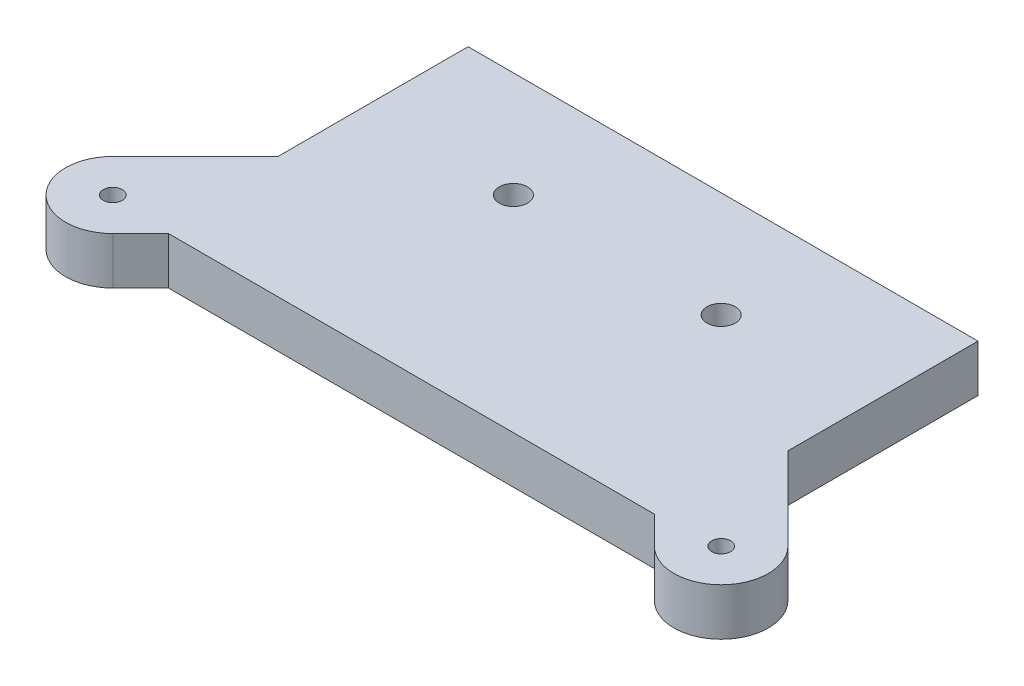
SolidWorks part; units mm, degrees
ref_plane "Front Plane" through (0, 0, 0) normal (0, 0, 1) x (1, 0, 0)
ref_plane "Top Plane" through (0, 0, 0) normal (0, 1, 0) x (1, 0, 0)
ref_plane "Right Plane" through (0, 0, 0) normal (1, 0, 0) x (0, 0, -1)
sketch "Sketch1" plane through (0, 0, 0) normal (0, 1, 0) x (1, 0, 0)
  line L1 (0, 0) -> (54, 0)
  line L2 (0, 0) -> (0, 33)
  line L3 (0, 33) -> (54, 33)
  line L4 (54, 0) -> (54, 33)
  dimension "D1" = 33
  dimension "D2" = 54
extrude "Boss-Extrude1" add sketch "Sketch1" along normal blind 5
sketch "Sketch2" plane through (0, 0, 0) normal (0, 1, 0) x (1, 0, 0)
  line L0 (62.1518, 21.8) -> (-9.5147, 21.8)
  line L1 (54, 33) -> (0, 33) construction
  line L3 (38, 29.3512) -> (38, 10.3952)
  line L4 (16, 29.3512) -> (16, 10.3952)
  line L5 (54, 0) -> (54, 33) construction
  line L6 (0, 33) -> (0, 0) construction
  line L7 (38, 21.8) -> (59.2132, 0.5868)
  line L8 (16, 21.8) -> (-5.2132, 0.5868)
  point P16 (0, 0)
  dimension "D1" = 11.2
  dimension "D2" = 16
  dimension "D3" = 16
  dimension "D4" = 30
  dimension "D5" = 30
  dimension "D6" = 45
  dimension "D7" = 45
sketch "Sketch4" plane through (0, 0, 0) normal (0, -1, 0) x (1, 0, 0)
  line L0 (62.7487, -4.1223) -> (54, -12.8711)
  line L1 (54, 0) -> (54, -33) construction
  line L2 (55.6777, 2.9487) -> (52.7289, 0)
  line L3 (0, 0) -> (54, 0) construction
  line L4 (54, -12.8711) -> (54, 0)
  line L5 (54, 0) -> (52.7289, 0)
  line L6 (-8.7487, -4.1223) -> (0, -12.8711)
  line L7 (0, -33) -> (0, 0) construction
  line L8 (-1.6777, 2.9487) -> (1.2711, 0)
  line L9 (0, -12.8711) -> (0, 0)
  line L10 (0, 0) -> (1.2711, 0)
  circle A0 centre (59.2132, -0.5868) radius 1
  circle A1 centre (-5.2132, -0.5868) radius 1
  arc A2 (62.7487, -4.1223) -> (55.6777, 2.9487) centre (59.2132, -0.5868) ccw
  arc A3 (-1.6777, 2.9487) -> (-8.7487, -4.1223) centre (-5.2132, -0.5868) ccw
  dimension "D1" = 2
  dimension "D2" = 2
  dimension "D3" = 10
  dimension "D4" = 10
  dimension "D5" = 135
  dimension "D6" = 135
extrude "Boss-Extrude2" add sketch "Sketch4" against normal blind 5
sketch "Sketch6" plane through (0, 0, 0) normal (0, -1, 0) x (1, 0, 0)
  circle A0 centre (38, -21.8) radius 1.5
  circle A1 centre (16, -21.8) radius 1.5
  dimension "D1" = 3
  dimension "D2" = 3
extrude "Cut-Extrude1" cut sketch "Sketch6" against normal blind 5
